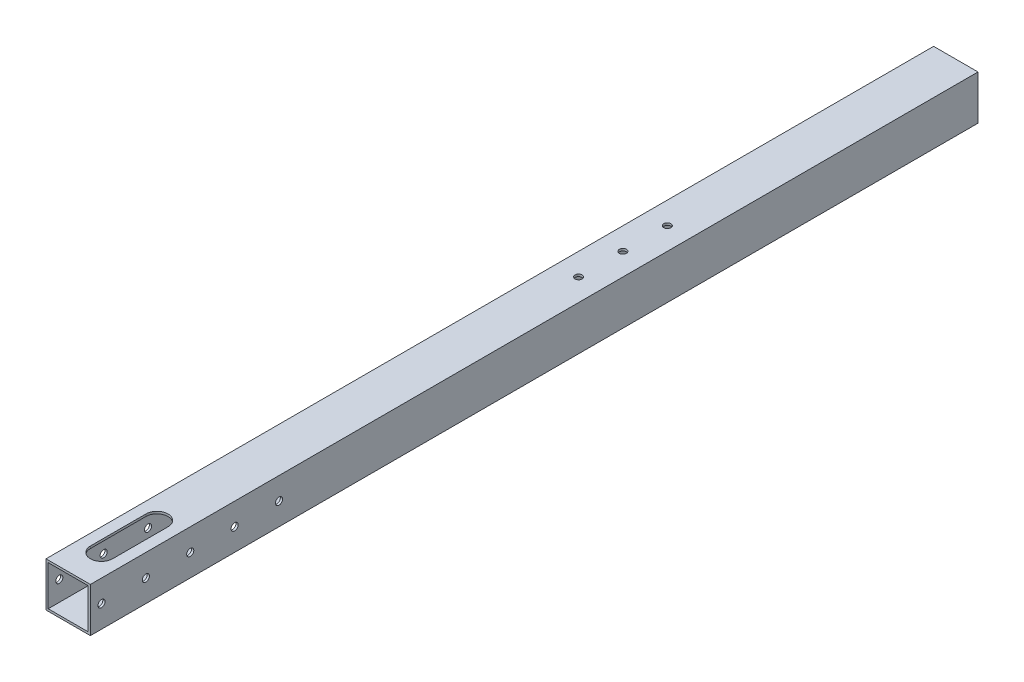
SolidWorks part; units mm, degrees
material "1060 合金"
ref_plane "前视基准面" through (0, 0, 0) normal (0, 0, 1) x (1, 0, 0)
ref_plane "上视基准面" through (0, 0, 0) normal (0, 1, 0) x (1, 0, 0)
ref_plane "右视基准面" through (0, 0, 0) normal (1, 0, 0) x (0, 0, -1)
other "Configuration Table"
sketch "草图1" plane through (0, 0, 0) normal (0, 0, 1) x (1, 0, 0)
  line L1 (0, 0) -> (20, 0)
  line L2 (0, 0) -> (0, -20)
  line L3 (0, -20) -> (20, -20)
  line L4 (20, 0) -> (20, -20)
  dimension "D1" = 20
  dimension "D2" = 20
extrude "拉伸-薄壁1" add sketch "草图1" along normal blind 400 thin
sketch "草图2" plane through (20, 0, 0) normal (1, 0, 0) x (0, 0, -1)
  line L0 (-400, -20) -> (-400, 0) construction
  line L1 (-400, -20) -> (0, -20) construction
  circle A0 centre (-395, -10) radius 1.6
  circle A1 centre (-375, -10) radius 1.6
  circle A2 centre (-355, -10) radius 1.6
  circle A3 centre (-335, -10) radius 1.6
  circle A4 centre (-315, -10) radius 1.6
  dimension "D3" = 3.2
  dimension "D1" = 5
  dimension "D2" = 10
  dimension "D4" = 5
extrude "切除-拉伸1" cut sketch "草图2" against normal through all
sketch "草图3" plane through (0, 0, 0) normal (0, 1, 0) x (1, 0, 0)
  line L0 (10, -360) -> (10, -385) construction
  line L1 (15, -360) -> (15, -385)
  line L2 (5, -360) -> (5, -385)
  line L3 (20, -400) -> (20, 0) construction
  line L4 (20, -400) -> (0, -400) construction
  arc A0 (15, -360) -> (5, -360) centre (10, -360) ccw
  arc A1 (5, -385) -> (15, -385) centre (10, -385) ccw
  point P2 (10, -372.5)
  dimension "D2" = 5
  dimension "D1" = 10
  dimension "D3" = 15
  dimension "D4" = 25
extrude "切除-拉伸2" cut sketch "草图3" against normal up to next
sketch "草图4" plane through (0, -20, 0) normal (0, -1, 0) x (1, 0, 0)
  line L0 (10, 335) -> (10, 315) construction
  line L1 (15, 335) -> (15, 315)
  line L2 (5, 335) -> (5, 315)
  line L4 (20, 400) -> (20, 0) construction
  line L5 (0, 400) -> (20, 400) construction
  arc A0 (15, 335) -> (5, 335) centre (10, 335) ccw
  arc A1 (5, 315) -> (15, 315) centre (10, 315) ccw
  point P2 (10, 325)
  dimension "D1" = 5
  dimension "D2" = 10
  dimension "D3" = 65
  dimension "D4" = 20
extrude "切除-拉伸3" cut sketch "草图4" against normal up to next
sketch "草图5" plane through (0, 0, 0) normal (0, 1, 0) x (1, 0, 0)
  line L0 (20, 0) -> (0, 0) construction
  line L1 (0, -400) -> (0, 0) construction
  circle A0 centre (10, -130) radius 1.6
  circle A1 centre (10, -150) radius 1.6
  circle A2 centre (10, -170) radius 1.6
  dimension "D2" = 3.2
  dimension "D1" = 130
  dimension "D3" = 10
  dimension "D4" = 3
extrude "切除-拉伸4" cut sketch "草图5" against normal through all
